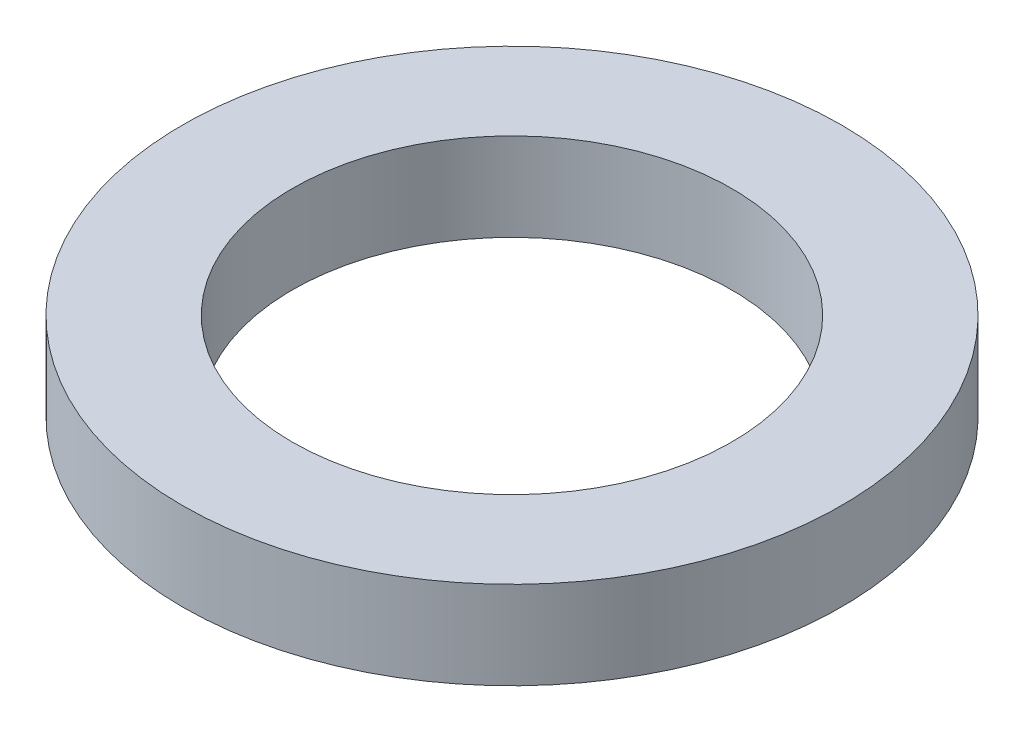
SolidWorks part; units mm, degrees
material "Nylon 101"
ref_plane "Front Plane" through (0, 0, 0) normal (0, 0, 1) x (1, 0, 0)
ref_plane "Top Plane" through (0, 0, 0) normal (0, 1, 0) x (1, 0, 0)
ref_plane "Right Plane" through (0, 0, 0) normal (1, 0, 0) x (0, 0, -1)
sketch "Sketch1" plane through (0, 0, 0) normal (0, 1, 0) x (1, 0, 0)
  circle A0 centre (0, 0) radius 9.525
  dimension "D1" = 19.05
extrude "Boss-Extrude1" add sketch "Sketch1" along normal blind 2.54
sketch "Sketch2" plane through (0, 2.54, 0) normal (0, 1, 0) x (1, 0, 0)
  circle A0 centre (0, 0) radius 6.35
  dimension "D1" = 12.7
extrude "Cut-Extrude1" cut sketch "Sketch2" against normal up to surface (2.54 mm away) up to face at (0, 0, 9.525)
